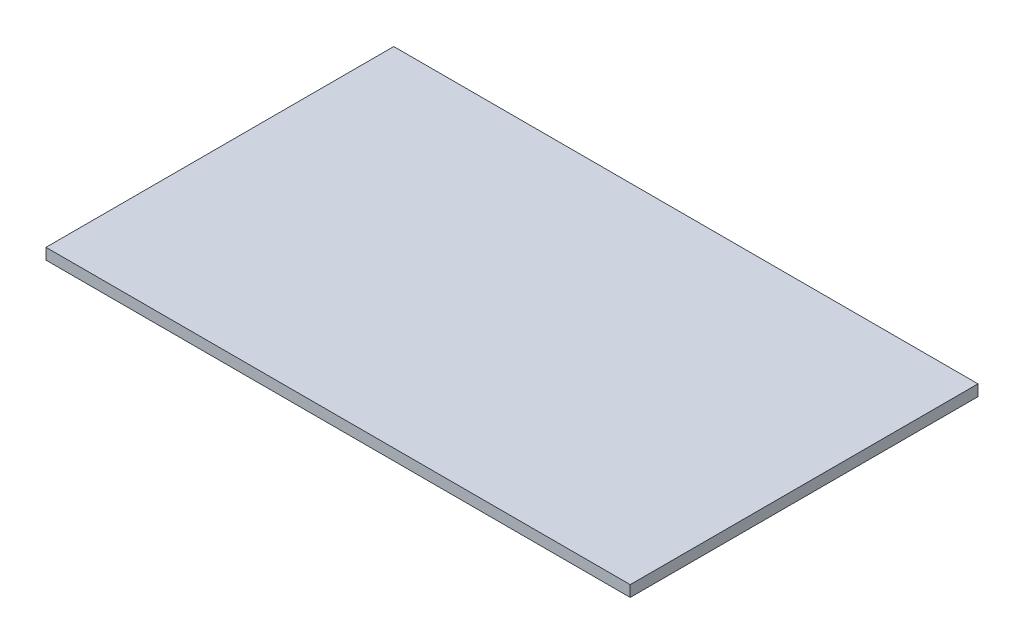
SolidWorks part; units mm, degrees
ref_plane "Front Plane" through (0, 0, 0) normal (0, 0, 1) x (1, 0, 0)
ref_plane "Top Plane" through (0, 0, 0) normal (0, 1, 0) x (1, 0, 0)
ref_plane "Right Plane" through (0, 0, 0) normal (1, 0, 0) x (0, 0, -1)
sketch "Sketch1" plane through (0, 0, 0) normal (0, 1, 0) x (1, 0, 0)
  line L1 (0, 0) -> (420, 0)
  line L2 (0, 0) -> (0, -250)
  line L3 (0, -250) -> (420, -250)
  line L4 (420, 0) -> (420, -250)
  dimension "D1" = 250
  dimension "D2" = 420
extrude "Boss-Extrude1" add sketch "Sketch1" along normal blind 8
